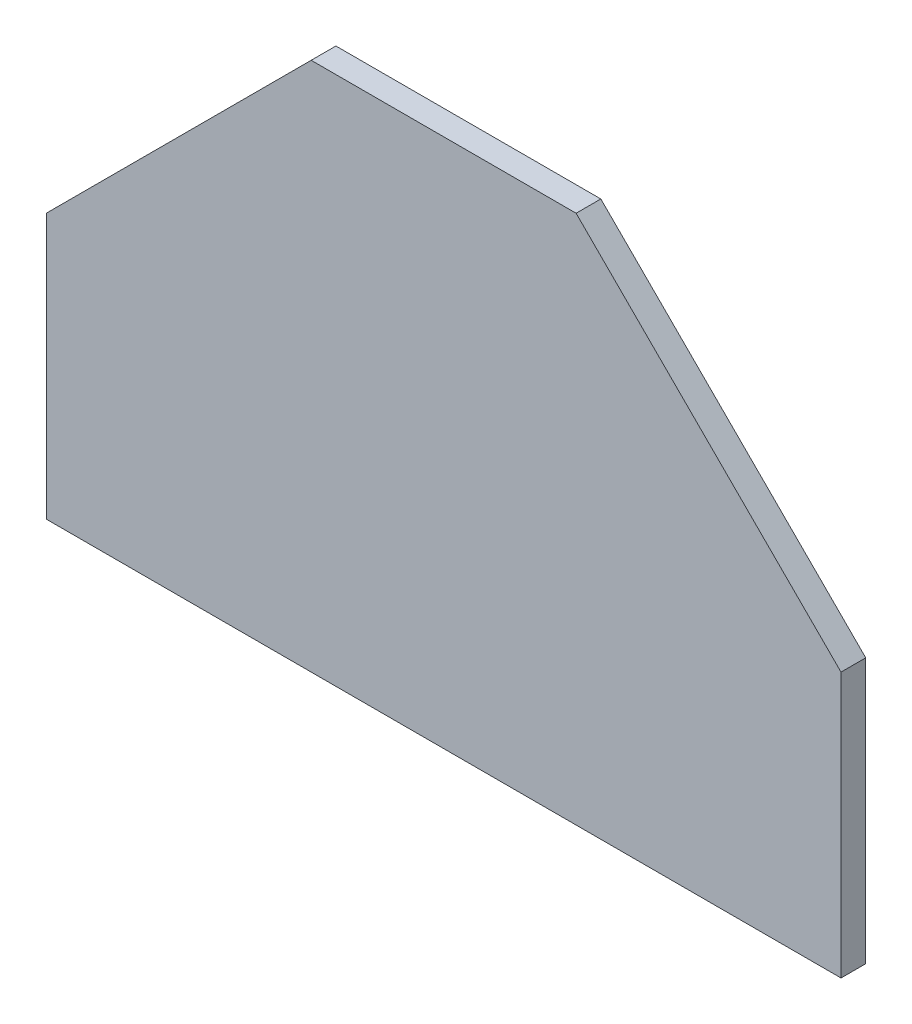
SolidWorks part; units mm, degrees
ref_plane "Front Plane" through (0, 0, 0) normal (0, 0, 1) x (1, 0, 0)
ref_plane "Top Plane" through (0, 0, 0) normal (0, 1, 0) x (1, 0, 0)
ref_plane "Right Plane" through (0, 0, 0) normal (1, 0, 0) x (0, 0, -1)
sketch "Sketch2" plane through (0, 0, 0) normal (0, 0, 1) x (1, 0, 0)
  line L0 (-16.7439, 49.749) -> (21.3561, 87.849)
  line L1 (-16.7439, 11.649) -> (97.5561, 11.649)
  line L2 (-16.7439, 11.649) -> (-16.7439, 49.749)
  line L3 (21.3561, 87.849) -> (59.4561, 87.849)
  line L4 (97.5561, 11.649) -> (97.5561, 49.749)
  line L5 (59.4561, 87.849) -> (97.5561, 49.749)
  point P1 (97.5561, 87.849)
  point P2 (-16.7439, 87.849)
  dimension "D1" = 76.2
  dimension "D2" = 114.3
extrude "Boss-Extrude1" add sketch "Sketch2" along normal blind 3.556 contours L0 L3 L5 L4 L1 L2
